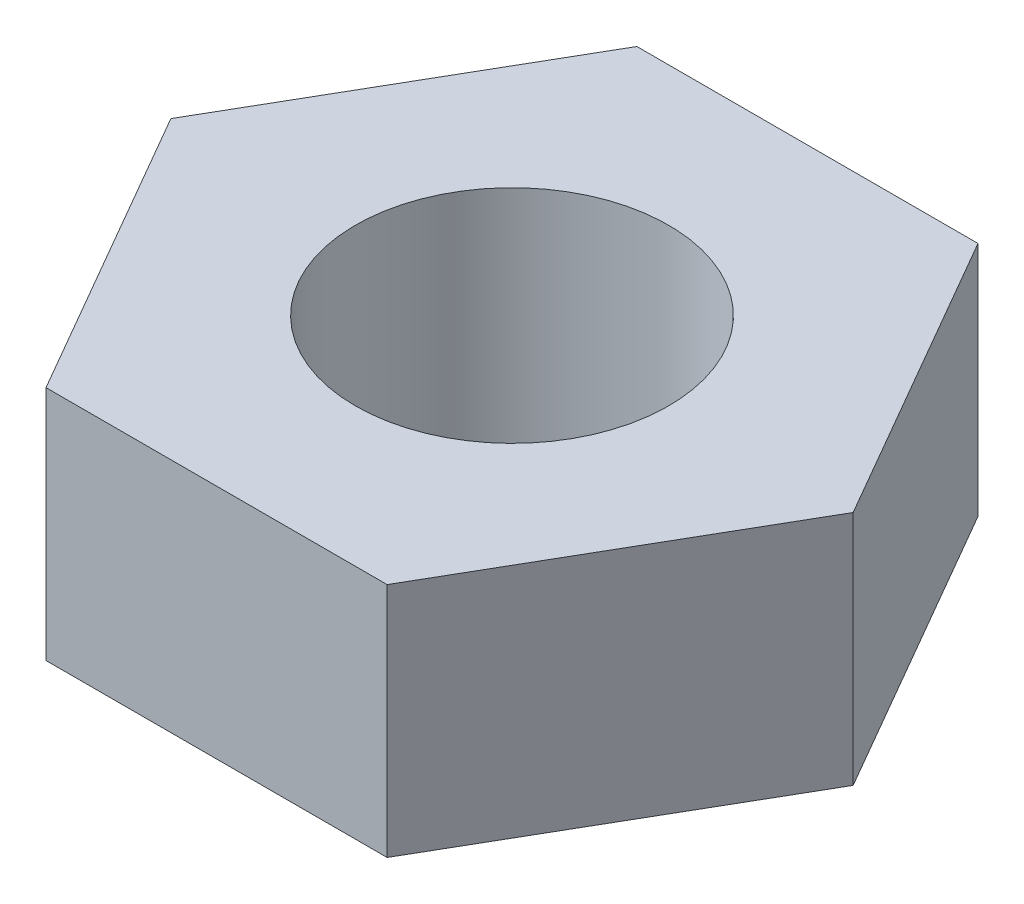
SolidWorks part; units mm, degrees
material "AISI Type A2 Tool Steel"
ref_plane "Front Plane" through (0, 0, 0) normal (0, 0, 1) x (1, 0, 0)
ref_plane "Top Plane" through (0, 0, 0) normal (0, 1, 0) x (1, 0, 0)
ref_plane "Right Plane" through (0, 0, 0) normal (1, 0, 0) x (0, 0, -1)
sketch "Sketch1" plane through (0, 0, 0) normal (0, 1, 0) x (1, 0, 0)
  line L1 (2.8868, 5) -> (-2.8868, 5)
  line L2 (-2.8868, 5) -> (-5.7735, 0)
  line L3 (-5.7735, 0) -> (-2.8868, -5)
  line L4 (-2.8868, -5) -> (2.8868, -5)
  line L5 (2.8868, -5) -> (5.7735, 0)
  line L6 (5.7735, 0) -> (2.8868, 5)
  circle A0 centre (0, 0) radius 5 construction
  circle A1 centre (0, 0) radius 2.65
  dimension "D1" = 5.3
  dimension "D2" = 10
extrude "Boss-Extrude1" add sketch "Sketch1" along normal blind 4
